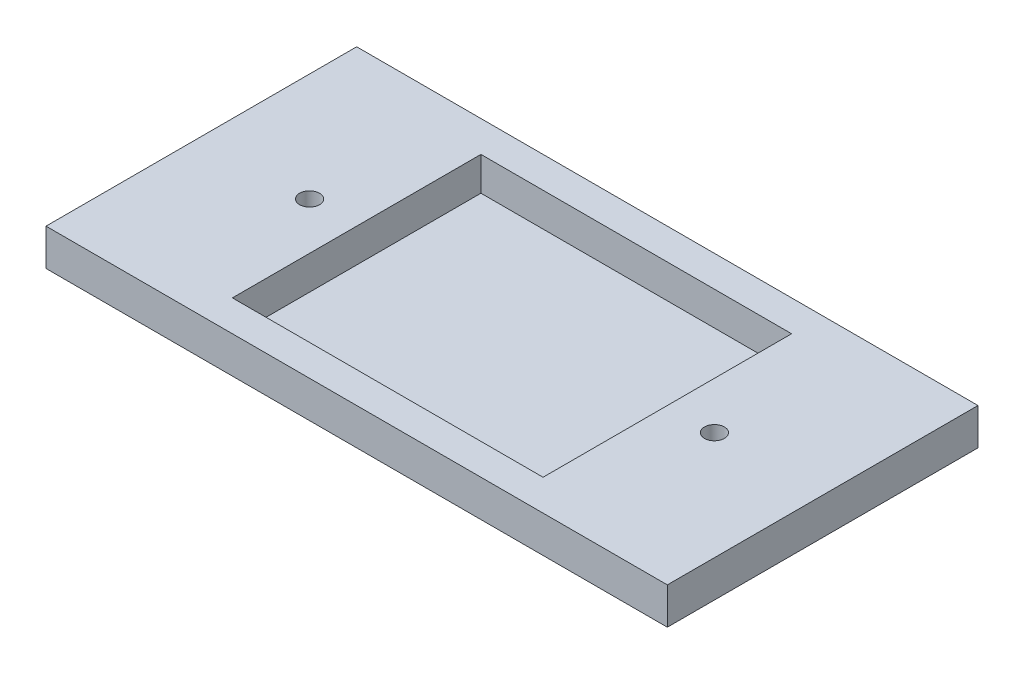
SolidWorks part; units mm, degrees
ref_plane "Front Plane" through (0, 0, 0) normal (0, 0, 1) x (1, 0, 0)
ref_plane "Top Plane" through (0, 0, 0) normal (0, 1, 0) x (1, 0, 0)
ref_plane "Right Plane" through (0, 0, 0) normal (1, 0, 0) x (0, 0, -1)
sketch "Sketch1" plane through (0, 0, 0) normal (0, 1, 0) x (1, 0, 0)
  line L1 (-50.8, -25.4) -> (50.8, -25.4)
  line L2 (-50.8, -25.4) -> (-50.8, 25.4)
  line L3 (-50.8, 25.4) -> (50.8, 25.4)
  line L4 (50.8, -25.4) -> (50.8, 25.4)
  line L5 (-50.8, -25.4) -> (50.8, 25.4) construction
  line L6 (-50.8, 25.4) -> (50.8, -25.4) construction
  point P0 (0, 0)
  dimension "D1" = 101.6
  dimension "D2" = 50.8
extrude "Boss-Extrude1" add sketch "Sketch1" along normal blind 6
sketch "Sketch2" plane through (0, 6, 0) normal (0, 1, 0) x (1, 0, 0)
  line L1 (-25.4, -20.32) -> (25.4, -20.32)
  line L2 (-25.4, -20.32) -> (-25.4, 20.32)
  line L3 (-25.4, 20.32) -> (25.4, 20.32)
  line L4 (25.4, -20.32) -> (25.4, 20.32)
  line L5 (-25.4, -20.32) -> (25.4, 20.32) construction
  line L6 (-25.4, 20.32) -> (25.4, -20.32) construction
  point P0 (0, 0)
  dimension "D1" = 40.64
  dimension "D2" = 50.8
extrude "Cut-Extrude1" cut sketch "Sketch2" against normal blind 5.5
sketch "Sketch3" plane through (0, 6, 0) normal (0, 1, 0) x (1, 0, 0)
  circle A0 centre (-33.1, 0) radius 1.6319
  dimension "D1" = 3.2639
extrude "Cut-Extrude2" cut sketch "Sketch3" against normal through all
sketch "Sketch4" plane through (0, 6, 0) normal (0, 1, 0) x (1, 0, 0)
  circle A0 centre (33.1, 0) radius 1.6319
  dimension "D1" = 3.2639
extrude "Cut-Extrude3" cut sketch "Sketch4" against normal through all
